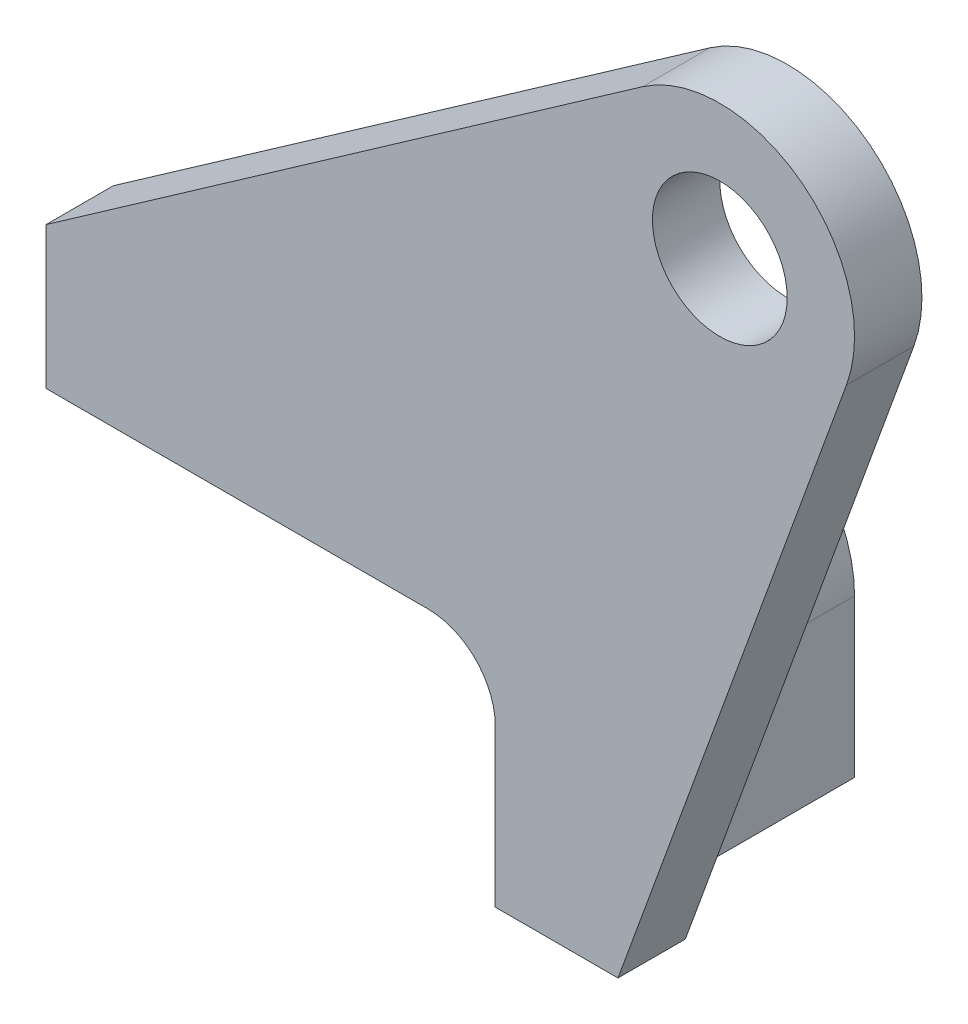
SolidWorks part; units mm, degrees
material "Простая углеродистая сталь"
ref_plane "Front" through (0, 0, 0) normal (0, 0, 1) x (1, 0, 0)
ref_plane "Top" through (0, 0, 0) normal (0, 1, 0) x (1, 0, 0)
ref_plane "Right" through (0, 0, 0) normal (1, 0, 0) x (0, 0, -1)
sketch "Эскиз1" plane through (0, 0, 0) normal (0, 0, 1) x (1, 0, 0)
  line L0 (-40, 0) -> (-6, 0)
  line L2 (10.9319, -20) -> (31.2763, 35.8958)
  line L3 (13.1171, 49.8298) -> (-40, 12.6368)
  line L4 (-40, 12.6368) -> (-40, 0)
  line L5 (0, -6) -> (0, -20)
  line L6 (0, -20) -> (10.9319, -20)
  arc A0 (31.2763, 35.8958) -> (13.1171, 49.8298) centre (20, 40) ccw
  circle A1 centre (20, 40) radius 6
  arc A2 (-6, 0) -> (0, -6) centre (-6, -6) cw
  point P16 (0, 0)
  dimension "D1" = 40
  dimension "D5" = 12
  dimension "D6" = 12
  dimension "D9" = 6
  dimension "D2" = 20
  dimension "D3" = 20
  dimension "D4" = 40
  dimension "D7" = 35
  dimension "D8" = 35
extrude "Бобышка-Вытянуть1" add sketch "Эскиз1" along normal blind 6
sketch "Эскиз2" plane through (0, 0, 0) normal (0, 0, 1) x (1, 0, 0)
  line L0 (-40, 0) -> (-6, 0) construction
  line L1 (0, -6) -> (0, -20) construction
  line L2 (-40, 0) -> (-6, 0)
  line L3 (0, -6) -> (0, -20)
  line L4 (-40, 6) -> (-6, 6)
  line L5 (6, -6) -> (6, -20)
  line L6 (0, -20) -> (6, -20)
  line L7 (-40, 0) -> (-40, 6)
  arc A0 (0, -6) -> (-6, 0) centre (-6, -6) ccw construction
  arc A1 (0, -6) -> (-6, 0) centre (-6, -6) ccw
  arc A2 (6, -6) -> (-6, 6) centre (-6, -6) ccw
  dimension "D1" = 6
extrude "Бобышка-Вытянуть2" add sketch "Эскиз2" against normal blind 20
fillet "Скругление1" radius 4 3 edges at (6, -13, 0) (2.4853, 2.4853, 0) (-23, 6, 0)
